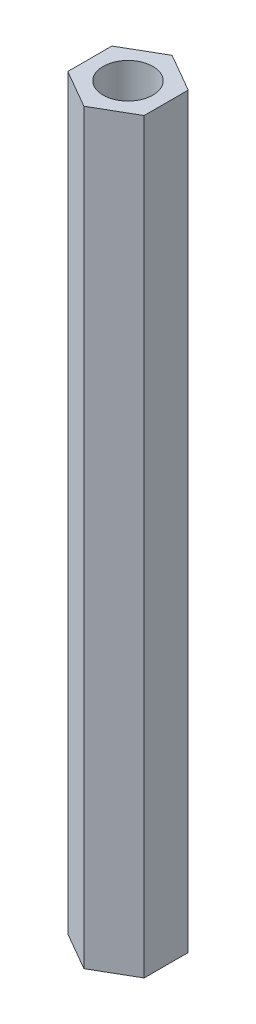
SolidWorks part; units mm, degrees
material "黄铜"
ref_plane "前视基准面" through (0, 0, 0) normal (0, 0, 1) x (1, 0, 0)
ref_plane "上视基准面" through (0, 0, 0) normal (0, 1, 0) x (1, 0, 0)
ref_plane "右视基准面" through (0, 0, 0) normal (1, 0, 0) x (0, 0, -1)
sketch "草图1" plane through (0, 0, 0) normal (0, 1, 0) x (1, 0, 0)
  line L1 (0, 2.6558) -> (-2.3, 1.3279)
  line L2 (-2.3, 1.3279) -> (-2.3, -1.3279)
  line L3 (-2.3, -1.3279) -> (0, -2.6558)
  line L4 (0, -2.6558) -> (2.3, -1.3279)
  line L5 (2.3, -1.3279) -> (2.3, 1.3279)
  line L6 (2.3, 1.3279) -> (0, 2.6558)
  circle A0 centre (0, 0) radius 2.3 construction
  circle A1 centre (0, 0) radius 1.5
  dimension "D2" = 3
  dimension "D1" = 4.6
extrude "凸台-拉伸1" add sketch "草图1" along normal blind 45
